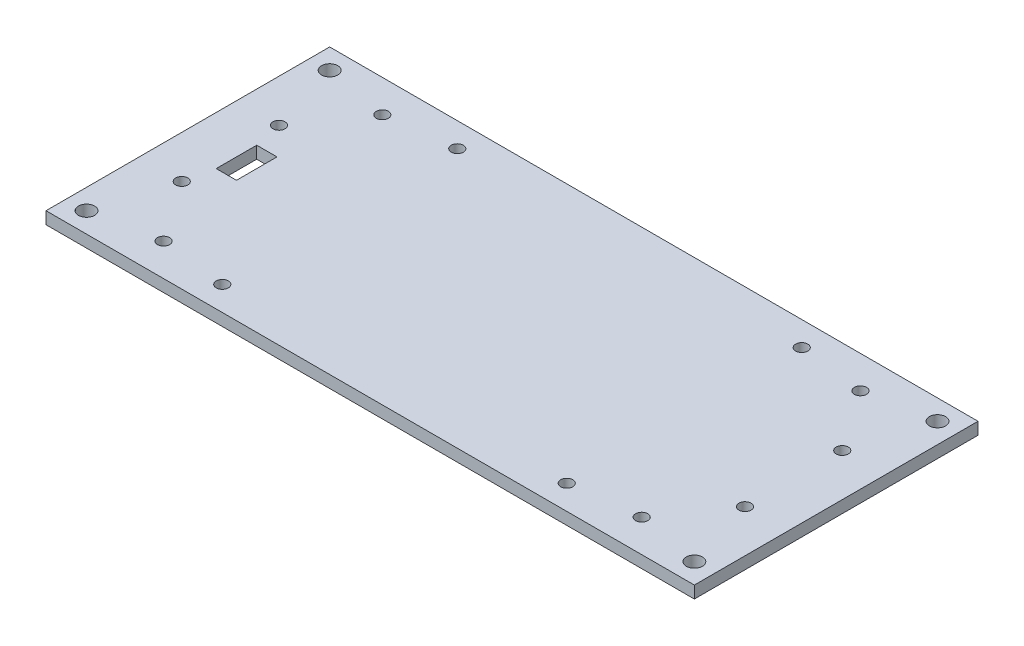
SolidWorks part; units mm, degrees
ref_plane "前视基准面" through (0, 0, 0) normal (0, 0, 1) x (1, 0, 0)
ref_plane "上视基准面" through (0, 0, 0) normal (0, 1, 0) x (1, 0, 0)
ref_plane "右视基准面" through (0, 0, 0) normal (1, 0, 0) x (0, 0, -1)
sketch "Sketch1" plane through (0, 0, 0) normal (0, 1, 0) x (1, 0, 0)
  line L1 (-80, 35) -> (80, 35)
  line L2 (-80, 35) -> (-80, -35)
  line L3 (-80, -35) -> (80, -35)
  line L4 (80, 35) -> (80, -35)
  line L5 (-80, 35) -> (80, -35) construction
  line L6 (-80, -35) -> (80, 35) construction
  point P0 (0, 0)
extrude "Extrude1" add sketch "Sketch1" along normal blind 3
sketch "Sketch2" plane through (0, 3, 0) normal (0, 1, 0) x (1, 0, 0)
  circle A0 centre (-75, 30) radius 2
  circle A1 centre (-75, -30) radius 2
  circle A2 centre (75, -30) radius 2
  circle A3 centre (75, 30) radius 2
extrude "Extrude2" cut sketch "Sketch2" against normal blind 120
sketch "Sketch3" plane through (0, 3, 0) normal (0, 1, 0) x (1, 0, 0)
  circle A0 centre (-59, 27) radius 1.5
  circle A1 centre (-59, -27) radius 1.5
  circle A2 centre (59, -27) radius 1.5
  circle A3 centre (59, 27) radius 1.5
  point P0 (0, 0)
extrude "Extrude3" cut sketch "Sketch3" against normal blind 10
sketch "Sketch4" plane through (0, 3, 0) normal (0, 1, 0) x (1, 0, 0)
  circle A0 centre (-69.5, 12) radius 1.5
  circle A1 centre (-69.5, -12) radius 1.5
  circle A2 centre (69.5, -12) radius 1.5
  circle A3 centre (69.5, 12) radius 1.5
extrude "Extrude4" cut sketch "Sketch4" against normal blind 10
sketch "Sketch5" plane through (0, 3, 0) normal (0, 1, 0) x (1, 0, 0)
  circle A0 centre (-42.5, 29) radius 1.5
  circle A1 centre (-42.5, -29) radius 1.5
  circle A2 centre (42.5, -29) radius 1.5
  circle A3 centre (42.5, 29) radius 1.5
  point P0 (0, 0)
extrude "Extrude5" cut sketch "Sketch5" against normal blind 10
sketch "Sketch6" plane through (0, 0, 0) normal (0, -1, 0) x (1, 0, 0)
  line L2 (-63, -5) -> (-68, -5)
  line L6 (-63, 5) -> (-63, -5)
  line L7 (-63, 5) -> (-68, 5)
  line L8 (-68, 5) -> (-68, -5)
extrude "Extrude6" cut sketch "Sketch6" against normal blind 5
